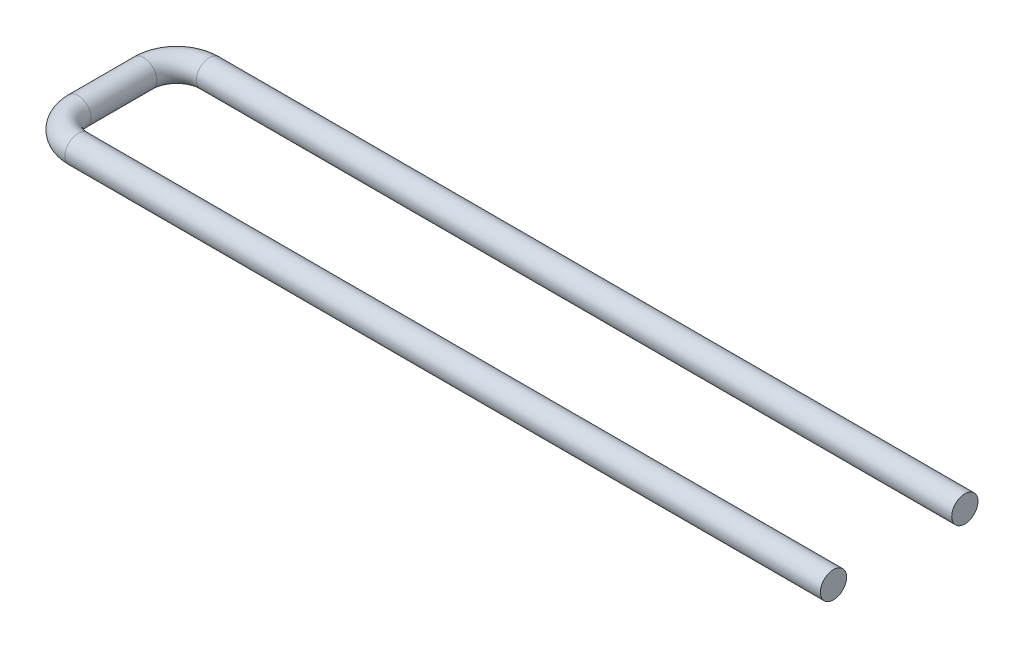
SolidWorks part; units mm, degrees
ref_plane "Płaszczyzna przednia" through (0, 0, 0) normal (0, 0, 1) x (1, 0, 0)
ref_plane "Płaszczyzna górna" through (0, 0, 0) normal (0, 1, 0) x (1, 0, 0)
ref_plane "Płaszczyzna prawa" through (0, 0, 0) normal (1, 0, 0) x (0, 0, -1)
sketch "Szkic1" plane through (0, 0, 0) normal (0, 1, 0) x (1, 0, 0)
  line L0 (0, 0) -> (-115, 0)
  line L1 (-120, 5) -> (-120, 15)
  line L2 (-115, 20) -> (0, 20)
  arc A0 (-115, 0) -> (-120, 5) centre (-115, 5) cw
  arc A1 (-120, 15) -> (-115, 20) centre (-115, 15) cw
  point P7 (-120, 0)
  point P10 (-120, 20)
  dimension "D3" = 5
  dimension "D1" = 120
  dimension "D2" = 20
sketch "Szkic2" plane through (0, 0, 0) normal (1, 0, 0) x (0, 0, -1)
  circle A0 centre (0, 0) radius 2
  dimension "D1" = 4
sweep "Wyciągnięcie po ścieżce1" add profiles "Szkic2" path "Szkic1"
